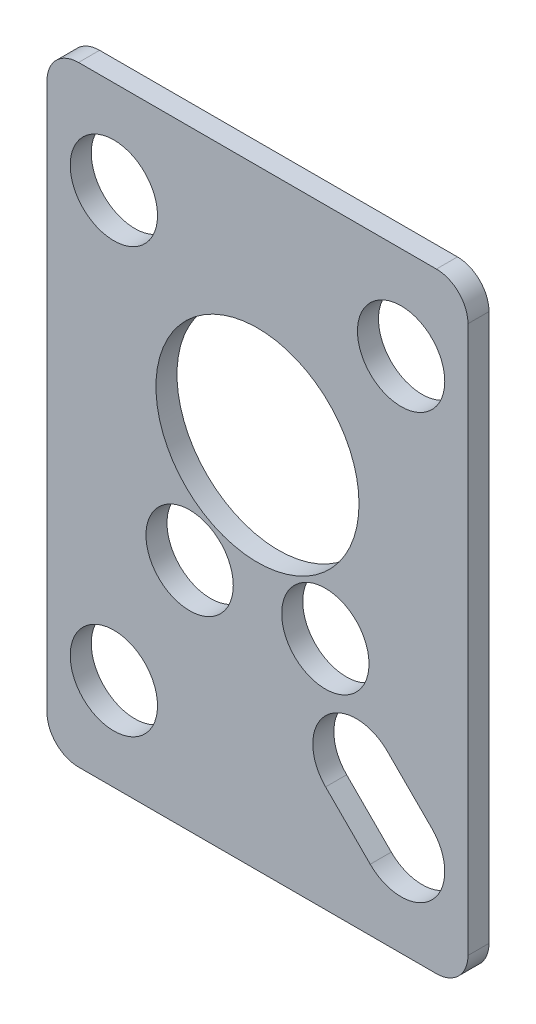
SolidWorks part; units mm, degrees
ref_plane "Front Plane" through (0, 0, 0) normal (0, 0, 1) x (1, 0, 0)
ref_plane "Top Plane" through (0, 0, 0) normal (0, 1, 0) x (1, 0, 0)
ref_plane "Right Plane" through (0, 0, 0) normal (1, 0, 0) x (0, 0, -1)
sketch "Sketch1" plane through (0, 0, 0) normal (0, 0, 1) x (1, 0, 0)
  line L0 (13.65, -20.2) -> (9.4074, -15.9574) construction
  line L3 (-17.005, 29) -> (17.005, 29) construction
  line L4 (17.005, -29) -> (-17.005, -29)
  line L5 (20.005, -26) -> (20.005, 26)
  line L6 (17.005, 29) -> (-17.005, 29)
  line L7 (-20.005, -26) -> (-20.005, 26)
  line L8 (20.005, -29) -> (-20.005, 29) construction
  line L9 (20.005, 29) -> (-20.005, -29) construction
  line L10 (-20.005, -26) -> (-20.005, 26) construction
  line L12 (10.7155, -23.1345) -> (6.4729, -18.8919)
  line L13 (16.5845, -17.2655) -> (12.3419, -13.0229)
  circle A0 centre (0, 6) radius 9.65
  circle A1 centre (13.65, 20.15) radius 4.15
  circle A2 centre (6.45, -6.7) radius 4.15
  circle A3 centre (-6.45, -6.7) radius 4.15
  circle A4 centre (-13.65, -20.2) radius 4.15
  circle A5 centre (-13.65, 20.15) radius 4.15
  arc A8 (-17.005, -29) -> (-20.005, -26) centre (-17.005, -26) cw
  arc A9 (17.005, -29) -> (20.005, -26) centre (17.005, -26) ccw
  arc A10 (20.005, 26) -> (17.005, 29) centre (17.005, 26) ccw
  arc A11 (-17.005, 29) -> (-20.005, 26) centre (-17.005, 26) ccw
  arc A12 (10.7155, -23.1345) -> (16.5845, -17.2655) centre (13.65, -20.2) ccw
  arc A13 (12.3419, -13.0229) -> (6.4729, -18.8919) centre (9.4074, -15.9574) ccw
  point P22 (11.5287, -18.0787)
  point P27 (0, 0)
  point P50 (0, 0)
  point P52 (0, 0)
  dimension "D1" = 8.3
  dimension "D2" = 8.3
  dimension "D3" = 19.3
  dimension "D4" = 3
  dimension "D5" = 45
  dimension "D6" = 6
extrude "Boss-Extrude1" add sketch "Sketch1" along normal blind 2
